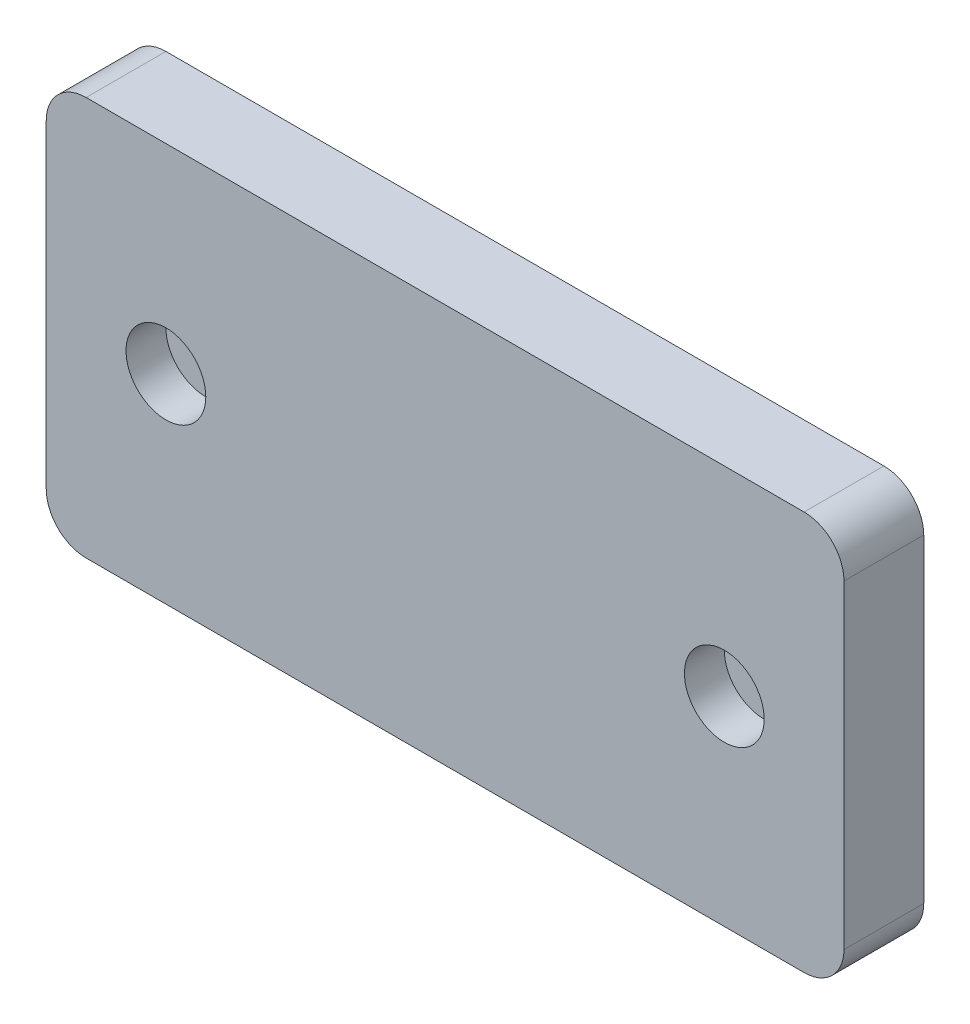
SolidWorks part; units mm, degrees
ref_plane "Front Plane" through (0, 0, 0) normal (0, 0, 1) x (1, 0, 0)
ref_plane "Top Plane" through (0, 0, 0) normal (0, 1, 0) x (1, 0, 0)
ref_plane "Right Plane" through (0, 0, 0) normal (1, 0, 0) x (0, 0, -1)
sketch "Sketch1" plane through (0, 0, 0) normal (0, 0, 1) x (1, 0, 0)
  line L1 (-5000, -2500) -> (5000, -2500)
  line L2 (-5000, -2500) -> (-5000, 2500)
  line L3 (-5000, 2500) -> (5000, 2500)
  line L4 (5000, -2500) -> (5000, 2500)
  line L5 (-5000, -2500) -> (5000, 2500) construction
  line L6 (-5000, 2500) -> (5000, -2500) construction
  point P0 (0, 0)
  dimension "D1" = 5000
  dimension "D2" = 2500
extrude "Boss-Extrude1" add sketch "Sketch1" along normal blind 1000
fillet "Fillet1" radius 500 1 edges at (-5000, 2500, 500)
fillet "Fillet2" radius 500 3 edges at (-5000, -2500, 500) (5000, -2500, 500) (5000, 2500, 500)
sketch "Sketch2" plane through (0, 0, 1000) normal (0, 0, 1) x (1, 0, 0)
  line L0 (4500, 2500) -> (-4500, 2500) construction
  circle A0 centre (-3500, 0) radius 500
  circle A1 centre (3500, 0) radius 500
  dimension "D3" = 1000
  dimension "D4" = 1000
  dimension "D1" = 3500
  dimension "D2" = 3500
  dimension "D5" = 2500
  dimension "D6" = 2500
extrude "Cut-Extrude1" cut sketch "Sketch2" against normal blind 500
